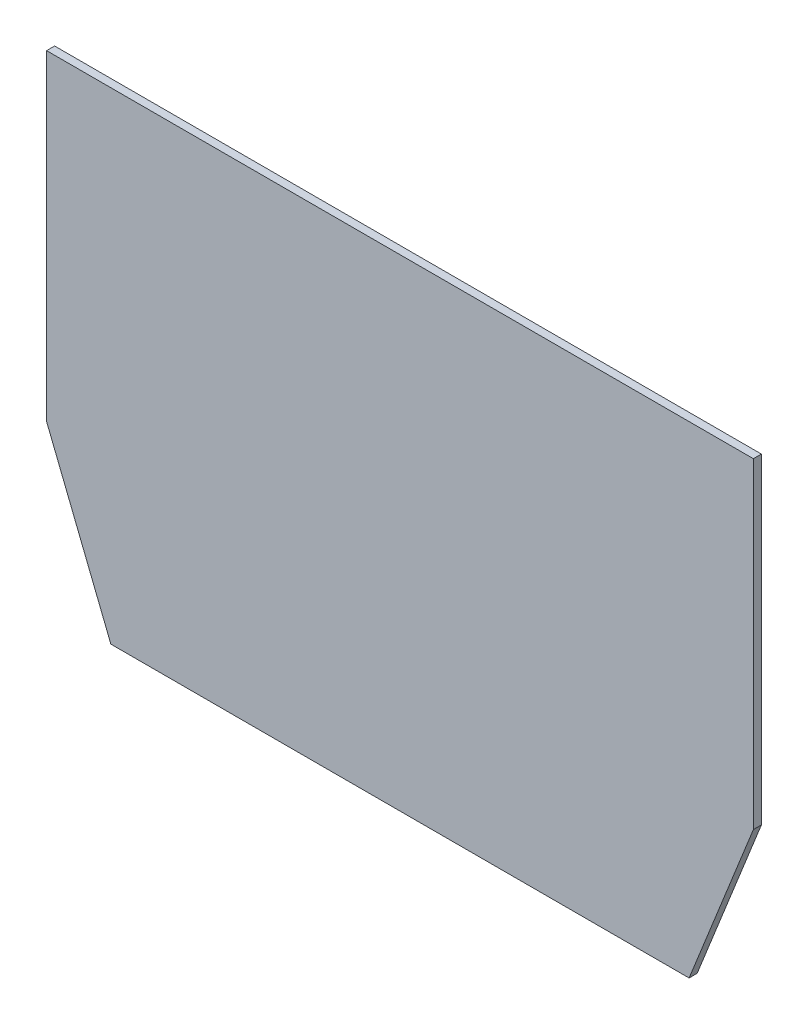
SolidWorks part; units mm, degrees
ref_plane "Front Plane" through (0, 0, 0) normal (0, 0, 1) x (1, 0, 0)
ref_plane "Top Plane" through (0, 0, 0) normal (0, 1, 0) x (1, 0, 0)
ref_plane "Right Plane" through (0, 0, 0) normal (1, 0, 0) x (0, 0, -1)
sketch "Sketch1" plane through (0, 0, 0) normal (0, 0, 1) x (1, 0, 0)
  line L0 (25.4, 0) -> (254, 0)
  line L1 (279.4, 63.5) -> (279.4, 190.5)
  line L2 (279.4, 190.5) -> (0, 190.5)
  line L3 (0, 190.5) -> (0, 63.5)
  line L4 (254, 0) -> (279.4, 63.5)
  line L5 (0, 63.5) -> (25.4, 0)
  dimension "D1" = 190.5
  dimension "D2" = 279.4
  dimension "D3" = 63.5
  dimension "D4" = 25.4
  dimension "D5" = 63.5
  dimension "D6" = 25.4
  dimension "D7" = 68.3916
  dimension "D8" = 111.801
extrude "Boss-Extrude1" add sketch "Sketch1" along normal blind 3.175
